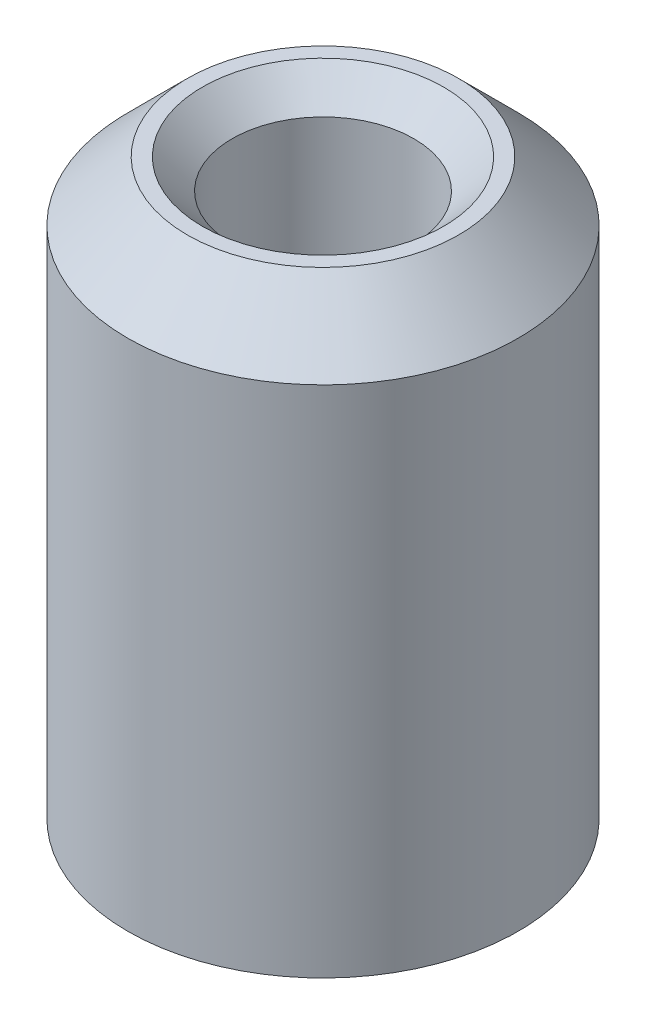
SolidWorks part; units mm, degrees
ref_plane "Front Plane" through (0, 0, 0) normal (0, 0, 1) x (1, 0, 0)
ref_plane "Top Plane" through (0, 0, 0) normal (0, 1, 0) x (1, 0, 0)
ref_plane "Right Plane" through (0, 0, 0) normal (1, 0, 0) x (0, 0, -1)
sketch "Sketch1" plane through (0, 0, 0) normal (0, 1, 0) x (1, 0, 0)
  circle A0 centre (0, 0) radius 3.05
  circle A1 centre (0, 0) radius 6.5532
  dimension "D1" = 6.1
  dimension "D2" = 13.1064
extrude "Boss-Extrude1" add sketch "Sketch1" along normal blind 19.24
chamfer "Chamfer1" distance 2 angle 45 1 edges at (0, 19.24, 6.5532)
chamfer "Chamfer2" distance 1 angle 45 1 edges at (0, 19.24, 3.05)
